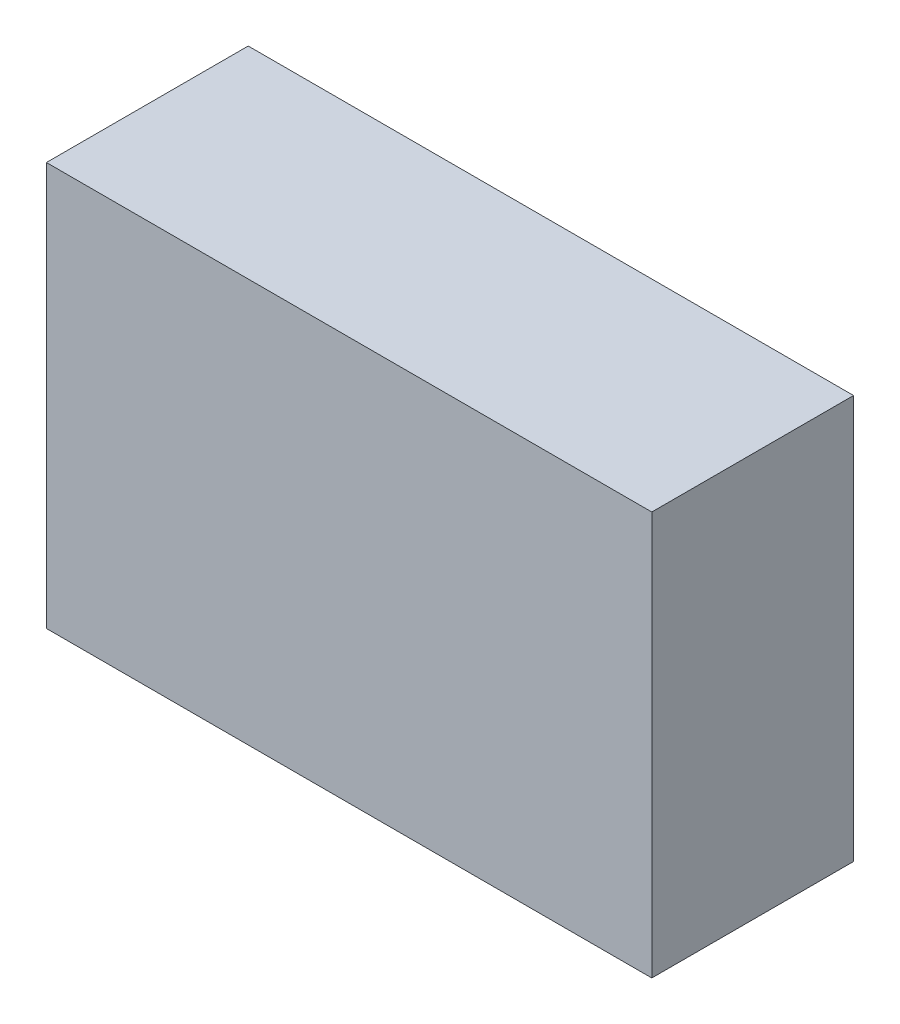
SolidWorks part; units mm, degrees
ref_plane "Front Plane" through (0, 0, 0) normal (0, 0, 1) x (1, 0, 0)
ref_plane "Top Plane" through (0, 0, 0) normal (0, 1, 0) x (1, 0, 0)
ref_plane "Right Plane" through (0, 0, 0) normal (1, 0, 0) x (0, 0, -1)
sketch "Sketch1" plane through (0, 0, 0) normal (0, 0, 1) x (1, 0, 0)
  line L1 (-50.4484, 37.5336) -> (9.5516, 37.5336)
  line L2 (-50.4484, 37.5336) -> (-50.4484, -2.4664)
  line L3 (-50.4484, -2.4664) -> (9.5516, -2.4664)
  line L4 (9.5516, 37.5336) -> (9.5516, -2.4664)
  line L5 (-50.4484, 37.5336) -> (9.5516, -2.4664) construction
  line L6 (-50.4484, -2.4664) -> (9.5516, 37.5336) construction
  point P0 (-20.4484, 17.5336)
  dimension "D1" = 60
  dimension "D2" = 40
extrude "Boss-Extrude1" add sketch "Sketch1" along normal blind 20
sketch "Sketch2" plane through (-50.4484, 0, 0) normal (-1, 0, 0) x (0, 0, 1)
  line L1 (0.0672, 19.7645) -> (2.6168, 19.7645)
  line L2 (0.0672, 19.7645) -> (0.0672, 15.3027)
  line L3 (0.0672, 15.3027) -> (2.6168, 15.3027)
  line L4 (2.6168, 19.7645) -> (2.6168, 15.3027)
  line L5 (0.0672, 19.7645) -> (2.6168, 15.3027) construction
  line L6 (0.0672, 15.3027) -> (2.6168, 19.7645) construction
  point P0 (1.342, 17.5336)
extrude "Cut-Extrude1" cut sketch "Sketch2" against normal blind 20
